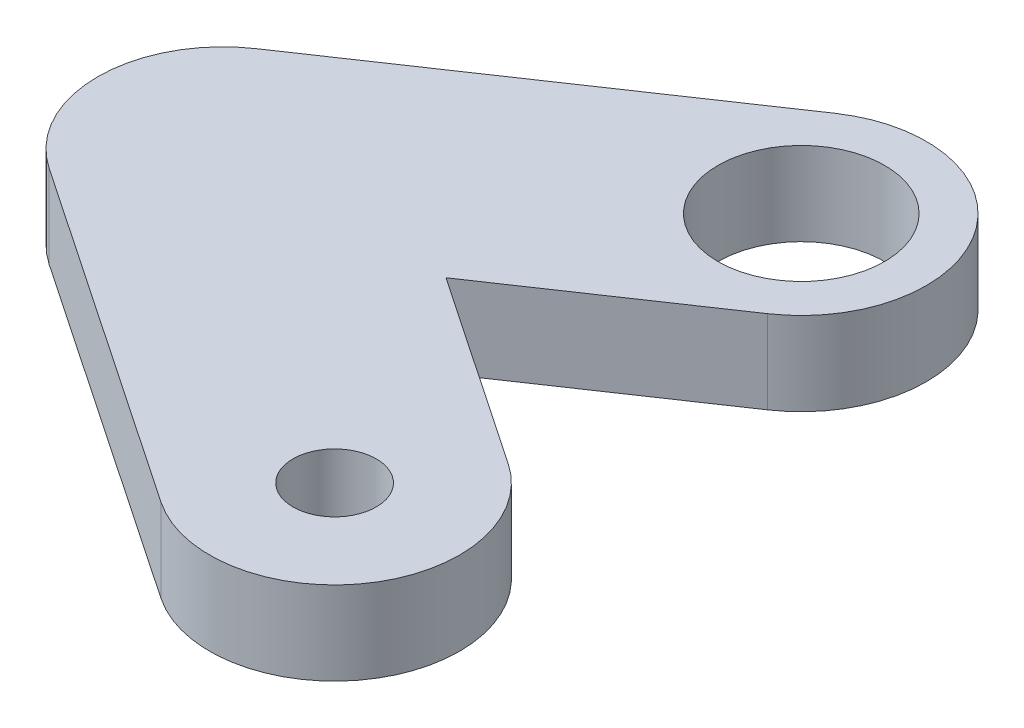
SolidWorks part; units mm, degrees
ref_plane "Front Plane" through (0, 0, 0) normal (1, 0, 0) x (0, 1, 0)
ref_plane "Top Plane" through (0, 0, 0) normal (0, 0, 1) x (0, 1, 0)
ref_plane "Right Plane" through (0, 0, 0) normal (0, 1, 0) x (-1, 0, 0)
sketch "Sketch1" plane through (0, 0, 0) normal (0, 1, 0) x (-1, 0, 0)
  line L2 (8.4, -12.4274) -> (49.8246, 15.5726)
  line L3 (8.4, 68.4274) -> (49.8246, 40.4274)
  line L4 (-8.4, 12.4274) -> (14.6389, 28)
  line L5 (-8.4, 43.5726) -> (14.6389, 28)
  arc A0 (-8.4, 12.4274) -> (8.4, -12.4274) centre (0, 0) ccw
  arc A1 (8.4, 68.4274) -> (-8.4, 43.5726) centre (0, 56) ccw
  circle A2 centre (0, 0) radius 10
  circle A3 centre (0, 56) radius 5
  arc A4 (49.8246, 15.5726) -> (49.8246, 40.4274) centre (41.4246, 28) ccw
  point P9 (-10.3992, 44.952)
  dimension "D1" = 30
  dimension "D2" = 30
  dimension "D4" = 20
  dimension "D5" = 10
  dimension "D6" = 30
  dimension "D3" = 56
  dimension "D7" = 28
  dimension "D8" = 50
extrude "Boss-Extrude1" add sketch "Sketch1" along normal blind 10
